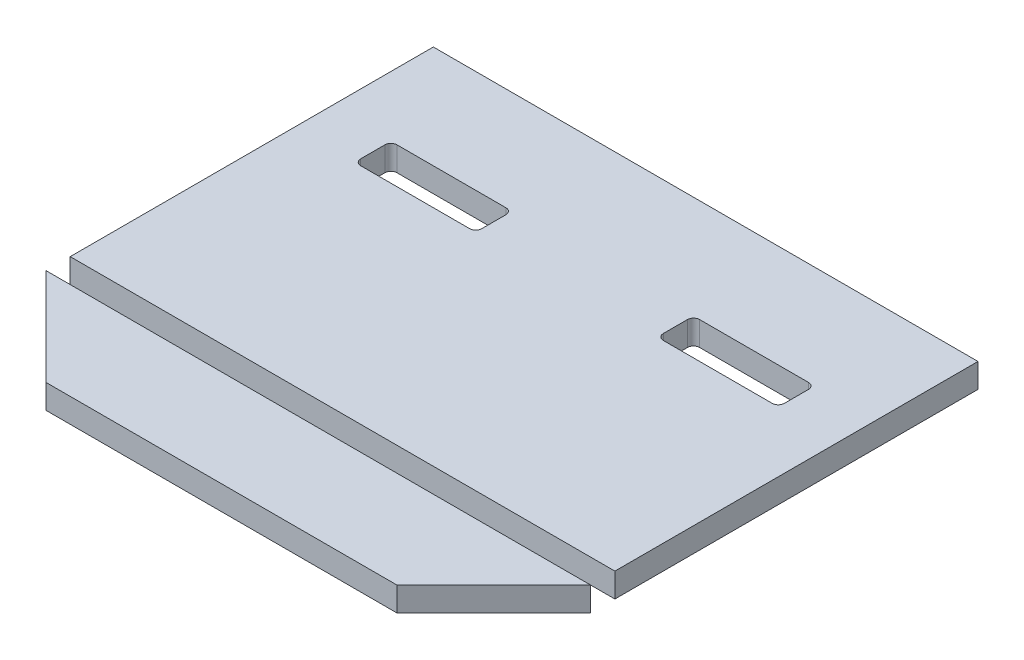
SolidWorks part; units mm, degrees
ref_plane "Front Plane" through (0, 0, 0) normal (0, 0, 1) x (1, 0, 0)
ref_plane "Top Plane" through (0, 0, 0) normal (0, 1, 0) x (1, 0, 0)
ref_plane "Right Plane" through (0, 0, 0) normal (1, 0, 0) x (0, 0, -1)
sketch "Sketch1" plane through (0, 0, 0) normal (0, 1, 0) x (1, 0, 0)
  line L1 (22.5, 15) -> (-22.5, 15)
  line L2 (22.5, 15) -> (22.5, -15)
  line L3 (22.5, -15) -> (-22.5, -15)
  line L4 (-22.5, 15) -> (-22.5, -15)
  line L7 (-22.5, 15) -> (-22.5, 5) construction
  line L11 (17, 3.5018) -> (8, 3.5018)
  line L12 (-17, 6.4982) -> (-8, 6.4982)
  line L13 (-17.5, 5.9982) -> (-17.5, 4.0018)
  line L14 (-17, 3.5018) -> (-8, 3.5018)
  line L15 (-7.5, 5.9982) -> (-7.5, 4.0018)
  line L18 (7.5, 5.9982) -> (7.5, 4.0018)
  line L19 (17, 6.4982) -> (8, 6.4982)
  line L20 (17.5, 5.9982) -> (17.5, 4.0018)
  line L23 (-22.5, -17) -> (22.5, -17)
  line L25 (-14.5, -25) -> (14.5, -25)
  line L26 (17.5, 5.9982) -> (17.5, 4.0018)
  line L27 (-22.5, -17) -> (-14.5, -25)
  line L28 (22.5, -17) -> (14.5, -25)
  line L29 (17, 3.5018) -> (8, 3.5018)
  line L30 (7.5, 5.9982) -> (7.5, 4.0018)
  line L31 (17, 6.4982) -> (8, 6.4982)
  arc A0 (-17.5, 5.9982) -> (-17, 6.4982) centre (-17, 5.9982) cw
  arc A1 (-17.5, 4.0018) -> (-17, 3.5018) centre (-17, 4.0018) ccw
  arc A2 (-7.5, 4.0018) -> (-8, 3.5018) centre (-8, 4.0018) cw
  arc A3 (-7.5, 5.9982) -> (-8, 6.4982) centre (-8, 5.9982) ccw
  arc A4 (17.5, 5.9982) -> (17, 6.4982) centre (17, 5.9982) ccw
  arc A5 (17.5, 4.0018) -> (17, 3.5018) centre (17, 4.0018) cw
  arc A6 (7.5, 4.0018) -> (8, 3.5018) centre (8, 4.0018) ccw
  arc A7 (7.5, 5.9982) -> (8, 6.4982) centre (8, 5.9982) cw
  point P0 (0, 0)
  point P8 (-12.5, 5)
extrude "Boss-Extrude7" add sketch "Sketch1" along normal blind 2 contours L1 L4 L3 L2 A3 L15 A2 L14 A1 L13 A0 L12 L18 A7 L19 A4 L20 A5 L11 A6 | L28 L23 L27 L25
